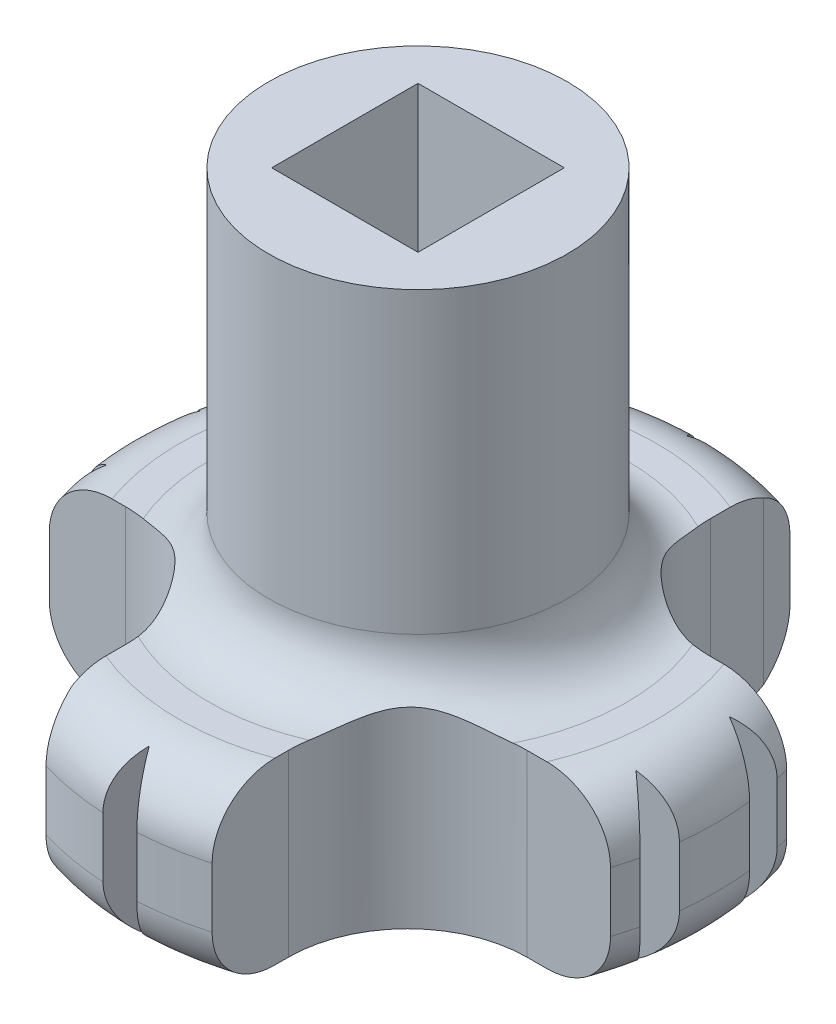
SolidWorks part; units mm, degrees
ref_plane "Front Plane" through (0, 0, 0) normal (0, 0, 1) x (1, 0, 0)
ref_plane "Top Plane" through (0, 0, 0) normal (0, 1, 0) x (1, 0, 0)
ref_plane "Right Plane" through (0, 0, 0) normal (1, 0, 0) x (0, 0, -1)
sketch "Sketch1" plane through (0, 0, 0) normal (1, 0, 0) x (0, 0, -1)
  line L0 (0, 0) -> (0, 15.3775) construction
  line L1 (0, 9) -> (2.5, 9)
  line L2 (2.5, 9) -> (2.5, 4)
  line L3 (3.5, 3) -> (4, 3)
  line L4 (5, 2) -> (5, 1)
  line L5 (4, 0) -> (0, 0)
  line L6 (0, 0) -> (0, 9)
  arc A0 (5, 1) -> (4, 0) centre (4, 1) cw
  arc A1 (4, 3) -> (5, 2) centre (4, 2) cw
  arc A2 (3.5, 3) -> (2.5, 4) centre (3.5, 4) cw
  point P10 (5, 0)
  point P13 (5, 3)
  point P16 (2.5, 3)
  dimension "D5" = 1
  dimension "D1" = 5
  dimension "D2" = 10
  dimension "D3" = 3
  dimension "D4" = 6
revolve "Revolve1" add sketch "Sketch1" angle 360 about L0
sketch "Sketch2" plane through (0, 9, 0) normal (0, 1, 0) x (1, 0, 0)
  line L1 (1.225, -1.225) -> (-1.225, -1.225)
  line L2 (1.225, -1.225) -> (1.225, 1.225)
  line L3 (1.225, 1.225) -> (-1.225, 1.225)
  line L4 (-1.225, -1.225) -> (-1.225, 1.225)
  line L5 (1.225, -1.225) -> (-1.225, 1.225) construction
  line L6 (1.225, 1.225) -> (-1.225, -1.225) construction
  point P0 (0, 0)
  dimension "D1" = 2.45
extrude "Cut-Extrude1" cut sketch "Sketch2" against normal blind 3
sketch "Sketch3" plane through (0, 3, 0) normal (0, 1, 0) x (1, 0, 0)
  line L0 (0, 4.5) -> (-1, 6.2321)
  line L1 (0, 4.5) -> (1, 6.2321)
  line L2 (1, 6.2321) -> (-1, 6.2321)
  line L3 (1.5391, 4.2286) -> (1.1918, 6.1982)
  line L4 (3.0712, 5.5142) -> (1.1918, 6.1982)
  line L5 (1.5391, 4.2286) -> (3.0712, 5.5142)
  line L6 (2.8925, 3.4472) -> (3.2398, 5.4168)
  line L7 (4.7719, 4.1312) -> (3.2398, 5.4168)
  line L8 (2.8925, 3.4472) -> (4.7719, 4.1312)
  line L9 (3.8971, 2.25) -> (4.8971, 3.9821)
  line L10 (5.8971, 2.25) -> (4.8971, 3.9821)
  line L11 (3.8971, 2.25) -> (5.8971, 2.25)
  line L12 (4.4316, 0.7814) -> (5.9637, 2.067)
  line L13 (6.311, 0.0974) -> (5.9637, 2.067)
  line L14 (4.4316, 0.7814) -> (6.311, 0.0974)
  line L15 (4.4316, -0.7814) -> (6.311, -0.0974)
  line L16 (5.9637, -2.067) -> (6.311, -0.0974)
  line L17 (4.4316, -0.7814) -> (5.9637, -2.067)
  line L18 (3.8971, -2.25) -> (5.8971, -2.25)
  line L19 (4.8971, -3.9821) -> (5.8971, -2.25)
  line L20 (3.8971, -2.25) -> (4.8971, -3.9821)
  line L21 (2.8925, -3.4472) -> (4.7719, -4.1312)
  line L22 (3.2398, -5.4168) -> (4.7719, -4.1312)
  line L23 (2.8925, -3.4472) -> (3.2398, -5.4168)
  line L24 (1.5391, -4.2286) -> (3.0712, -5.5142)
  line L25 (1.1918, -6.1982) -> (3.0712, -5.5142)
  line L26 (1.5391, -4.2286) -> (1.1918, -6.1982)
  line L27 (0, -4.5) -> (1, -6.2321)
  line L28 (-1, -6.2321) -> (1, -6.2321)
  line L29 (0, -4.5) -> (-1, -6.2321)
  line L30 (-1.5391, -4.2286) -> (-1.1918, -6.1982)
  line L31 (-3.0712, -5.5142) -> (-1.1918, -6.1982)
  line L32 (-1.5391, -4.2286) -> (-3.0712, -5.5142)
  line L33 (-2.8925, -3.4472) -> (-3.2398, -5.4168)
  line L34 (-4.7719, -4.1312) -> (-3.2398, -5.4168)
  line L35 (-2.8925, -3.4472) -> (-4.7719, -4.1312)
  line L36 (-3.8971, -2.25) -> (-4.8971, -3.9821)
  line L37 (-5.8971, -2.25) -> (-4.8971, -3.9821)
  line L38 (-3.8971, -2.25) -> (-5.8971, -2.25)
  line L39 (-4.4316, -0.7814) -> (-5.9637, -2.067)
  line L40 (-6.311, -0.0974) -> (-5.9637, -2.067)
  line L41 (-4.4316, -0.7814) -> (-6.311, -0.0974)
  line L42 (-4.4316, 0.7814) -> (-6.311, 0.0974)
  line L43 (-5.9637, 2.067) -> (-6.311, 0.0974)
  line L44 (-4.4316, 0.7814) -> (-5.9637, 2.067)
  line L45 (-3.8971, 2.25) -> (-5.8971, 2.25)
  line L46 (-4.8971, 3.9821) -> (-5.8971, 2.25)
  line L47 (-3.8971, 2.25) -> (-4.8971, 3.9821)
  line L48 (-2.8925, 3.4472) -> (-4.7719, 4.1312)
  line L49 (-3.2398, 5.4168) -> (-4.7719, 4.1312)
  line L50 (-2.8925, 3.4472) -> (-3.2398, 5.4168)
  line L51 (-1.5391, 4.2286) -> (-3.0712, 5.5142)
  line L52 (-1.1918, 6.1982) -> (-3.0712, 5.5142)
  line L53 (-1.5391, 4.2286) -> (-1.1918, 6.1982)
  point P2 (0, 6.2321)
  point P58 (0, 0)
  dimension "D1" = 2
  dimension "D2" = 4.5
  dimension "D3" = 18
extrude "Cut-Extrude2" cut sketch "Sketch3" against normal blind 3
sketch "Sketch4" plane through (0, 3, 0) normal (0, 1, 0) x (1, 0, 0)
  line L1 (-8.3628, 8.5352) -> (-1.3628, 8.5352)
  line L2 (-8.3628, 8.5352) -> (-8.3628, 1.5352)
  line L3 (-8.3628, 1.5352) -> (-3.3628, 1.5352)
  line L4 (-1.3628, 8.5352) -> (-1.3628, 3.5352)
  line L5 (-8.3628, 8.5352) -> (-1.3628, 1.5352) construction
  line L6 (-8.3628, 1.5352) -> (-1.3628, 8.5352) construction
  arc A0 (-3.3628, 1.5352) -> (-1.3628, 3.5352) centre (-3.3628, 3.5352) ccw
  point P0 (-4.8628, 5.0352)
  dimension "D1" = 2
  dimension "D2" = 7
  dimension "D3" = 7
extrude "Cut-Extrude3" cut sketch "Sketch4" against normal through all both and the other way through all
pattern_circular "CirPattern1" count 4 over 360 about axis through (0, 0, 0) along (0, 1, 0) of "Cut-Extrude3"
